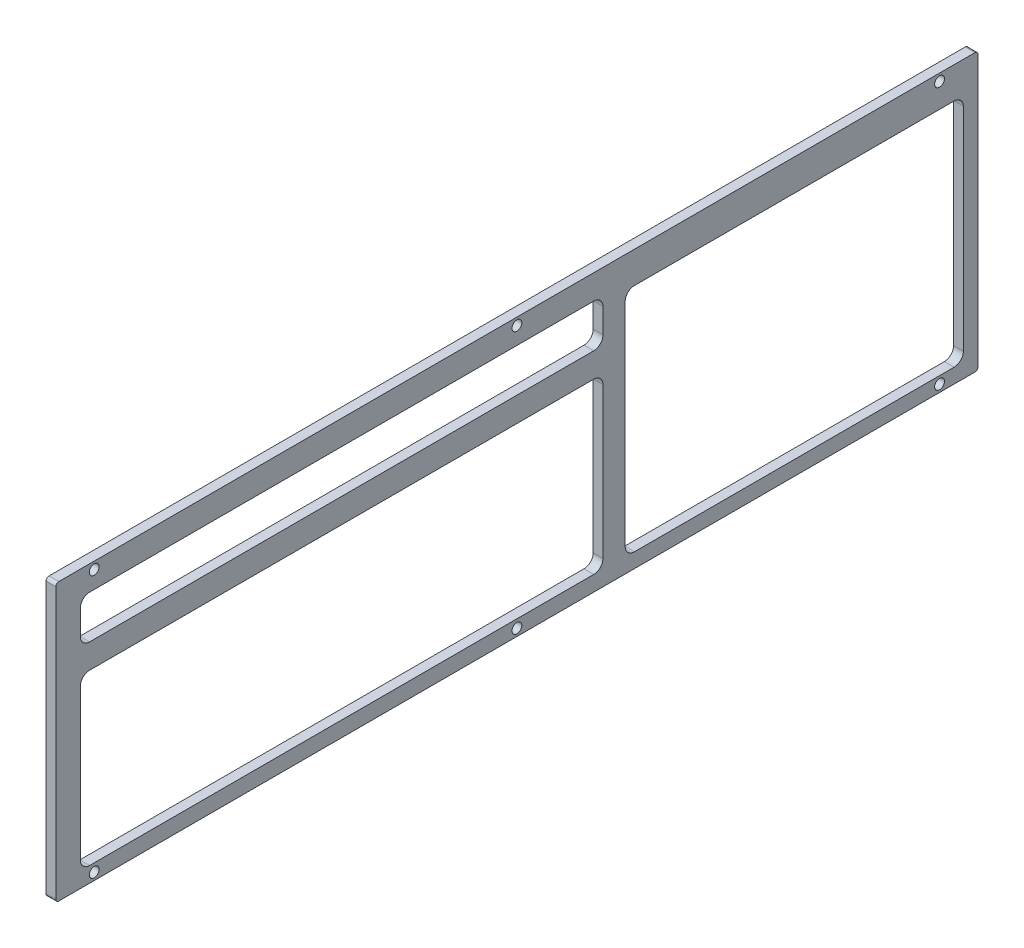
SolidWorks part; units mm, degrees
material "6061 Alloy"
ref_plane "Front Plane" through (0, 0, 0) normal (0, 0, 1) x (1, 0, 0)
ref_plane "Top Plane" through (0, 0, 0) normal (0, 1, 0) x (1, 0, 0)
ref_plane "Right Plane" through (0, 0, 0) normal (1, 0, 0) x (0, 0, -1)
sketch "Sketch2" plane through (0, 0, 0) normal (1, 0, 0) x (0, 0, -1)
  line L1 (-150, -45) -> (150, -45)
  line L2 (-150, -45) -> (-150, 45)
  line L3 (-150, 45) -> (150, 45)
  line L4 (150, -45) -> (150, 45)
  line L5 (-150, -45) -> (150, 45) construction
  line L6 (-150, 45) -> (150, -45) construction
  point P0 (0, 0)
  dimension "D1" = 300
  dimension "D2" = 90
extrude "Boss-Extrude1" add sketch "Sketch2" along normal blind 3.175
sketch "Sketch4" plane through (3.175, 0, 0) normal (1, 0, 0) x (0, 0, -1)
  line L0 (-150, 45) -> (-150, -45) construction
  line L12 (-142, 15) -> (28, 15)
  line L13 (-150, -45) -> (150, -45) construction
  line L14 (-142, 15) -> (-142, -40)
  line L15 (-142, -40) -> (28, -40)
  line L16 (28, 15) -> (28, -40)
  line L17 (150, -45) -> (150, 45) construction
  line L18 (145.2375, 34.7625) -> (35.2375, 34.7625)
  line L20 (145.2375, 34.7625) -> (145.2375, -40.2375)
  line L21 (145.2375, -40.2375) -> (35.2375, -40.2375)
  line L22 (35.2375, 34.7625) -> (35.2375, -40.2375)
  line L35 (150, 45) -> (-150, 45) construction
  line L36 (-142, 23) -> (28, 23)
  line L37 (-142, 23) -> (-142, 37)
  line L38 (-142, 37) -> (28, 37)
  line L39 (28, 23) -> (28, 37)
  dimension "D1" = 4.7625
  dimension "D4" = 75
  dimension "D5" = 8
  dimension "D6" = 170
  dimension "D7" = 8
  dimension "D8" = 5
  dimension "D9" = 55
  dimension "D2" = 110
  dimension "D3" = 4.7625
  dimension "D10" = 8
extrude "Cut-Extrude2" cut sketch "Sketch4" against normal through all
sketch "Sketch6" plane through (3.175, 0, 0) normal (1, 0, 0) x (0, 0, -1)
  line L0 (150, 45) -> (-150, 45) construction
  line L1 (-137.5, -42.6188) -> (137.5, -42.6188) construction
  line L2 (-137.5, -42.6188) -> (-137.5, 42.6188) construction
  line L3 (-137.5, 42.6188) -> (137.5, 42.6188) construction
  line L4 (137.5, -42.6188) -> (137.5, 42.6188) construction
  line L5 (-137.5, -42.6188) -> (137.5, 42.6188) construction
  line L6 (-137.5, 42.6188) -> (137.5, -42.6188) construction
  point P0 (0, 0)
  dimension "D1" = 275
  dimension "D2" = 2.3813
hole_wizard "M3 Clearance Hole1" positions "Sketch7" profile "Sketch8" hole size "M3" standard "ANSI Metric" end condition through all
sketch "Sketch7" plane through (3.175, 0, 0) normal (1, 0, 0) x (0, 0, -1)
  line L0 (-137.5, 42.6188) -> (137.5, 42.6188) construction
  line L1 (-137.5, -42.6188) -> (137.5, -42.6188) construction
  point P0 (-137.5, 42.6188)
  point P3 (0, 42.6188)
  point P7 (137.5, 42.6188)
  point P10 (137.5, -42.6188)
  point P13 (0, -42.6188)
  point P17 (-137.5, -42.6188)
sketch "Sketch8" plane through (3.175, 42.6188, 137.5) normal (0, 1, 0) x (0, 0, -1)
  line L0 (0, 0) -> (0, 3.175)
  line L1 (0, 3.175) -> (1.6, 3.175)
  line L2 (1.6, 3.175) -> (1.6, 0)
  line L5 (1.6, 0) -> (0, 0)
  line L11 (0, -6.35) -> (0, 107.95) construction
  dimension "Thru Hole Dia." = 3.2
  dimension "Thru Hole Depth" = 3.175
fillet "Fillet1" radius 3 12 edges at (1.5875, 15, 142) (1.5875, 15, -28) (1.5875, -40, -28) (1.5875, -40, 142) (1.5875, -40.2375, -145.2375) (1.5875, 34.7625, -35.2375) (1.5875, 34.7625, -145.2375) (1.5875, -40.2375, -35.2375) (1.5875, 37, 142) (1.5875, 37, -28) (1.5875, 23, -28) (1.5875, 23, 142)
fillet "Fillet2" radius 1 4 edges at (1.5875, -45, 150) (1.5875, 45, 150) (1.5875, -45, -150) (1.5875, 45, -150)
